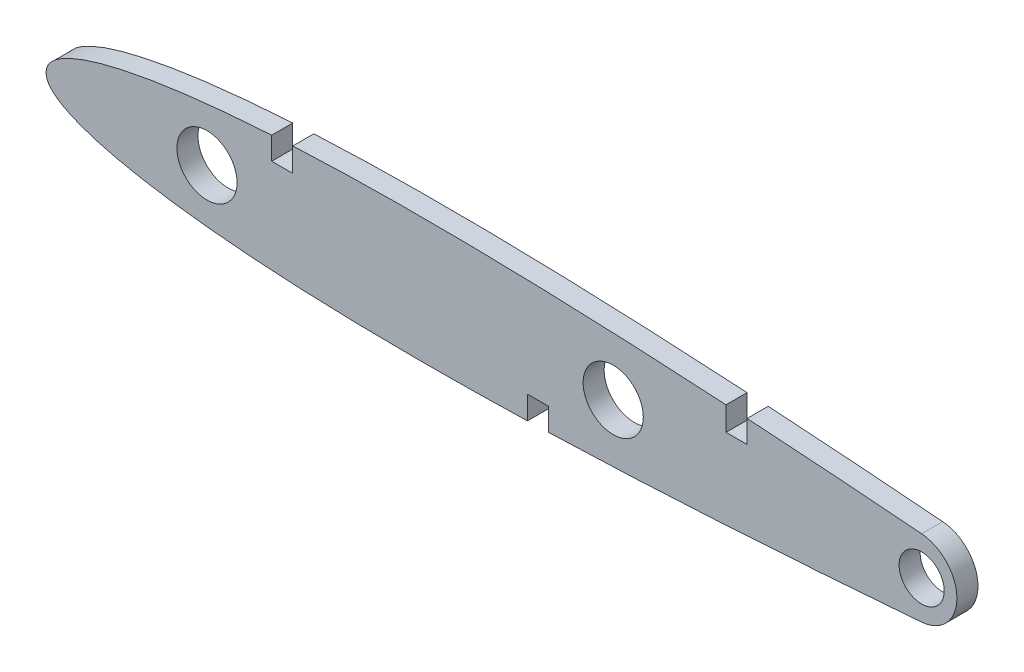
SolidWorks part; units mm, degrees
material "Фанера"
ref_plane "Спереди" through (0, 0, 0) normal (0, 0, 1) x (1, 0, 0)
ref_plane "Сверху" through (0, 0, 0) normal (0, 1, 0) x (1, 0, 0)
ref_plane "Справа" through (0, 0, 0) normal (1, 0, 0) x (0, 0, -1)
curve "Кривая1"
  spline degree 3 poles (200, 0.1747, 0) (199.6007, 0.2213, 0) (198.4854, 0.3514, 0) (196.462, 0.5838, 0) (193.7856, 0.8861, 0) (190.6579, 1.2319, 0) (187.1764, 1.6078, 0) (183.4067, 2.0045, 0) (179.3984, 2.4149, 0) (175.1909, 2.8335, 0) (170.8176, 3.2558, 0) (166.3067, 3.6778, 0) (161.6831, 4.0963, 0) (156.9692, 4.5083, 0) (152.1848, 4.9111, 0) (147.3484, 5.3022, 0) (142.4768, 5.6794, 0) (137.5855, 6.0402, 0) (132.6892, 6.3824, 0) (127.8016, 6.7038, 0) (122.9356, 7.0023, 0) (118.1034, 7.2757, 0) (113.3167, 7.5219, 0) (108.5864, 7.7388, 0) (103.9232, 7.9245, 0) (99.3373, 8.0772, 0) (94.8383, 8.1952, 0) (90.4357, 8.2769, 0) (86.1385, 8.321, 0) (81.9555, 8.3264, 0) (77.8951, 8.2921, 0) (73.9656, 8.2177, 0) (70.1749, 8.1027, 0) (66.5308, 7.947, 0) (63.0408, 7.751, 0) (59.7122, 7.515, 0) (56.5522, 7.2398, 0) (53.5677, 6.9266, 0) (50.7656, 6.5764, 0) (48.1524, 6.1907, 0) (45.7346, 5.7713, 0) (43.5185, 5.3197, 0) (41.5102, 4.8379, 0) (39.7154, 4.3278, 0) (38.1397, 3.791, 0) (36.7878, 3.2294, 0) (35.6652, 2.6441, 0) (34.771, 2.0345, 0) (34.119, 1.3968, 0) (33.6837, 0.7187, 0) (33.627, 0.2317, 0) (33.6, 0, 0) knots 0 0 0 0 0.007145 0.019956 0.036196 0.055011 0.075879 0.098429 0.122376 0.147488 0.173572 0.20046 0.228005 0.256076 0.284555 0.313333 0.34231 0.371393 0.400496 0.429538 0.458442 0.487136 0.515552 0.543624 0.57129 0.598491 0.62517 0.651272 0.676746 0.701542 0.725611 0.748908 0.771388 0.793008 0.813728 0.833508 0.85231 0.870097 0.886836 0.902493 0.917037 0.930441 0.94268 0.953734 0.96359 0.972247 0.979722 0.986065 0.991385 0.995901 1 1 1 1
curve "Кривая2"
  spline degree 3 poles (33.6, 0, 0) (33.627, -0.2317, 0) (33.6837, -0.7187, 0) (34.119, -1.3968, 0) (34.771, -2.0345, 0) (35.6652, -2.6441, 0) (36.7878, -3.2294, 0) (38.1397, -3.791, 0) (39.7154, -4.3278, 0) (41.5102, -4.8379, 0) (43.5185, -5.3197, 0) (45.7346, -5.7713, 0) (48.1524, -6.1907, 0) (50.7656, -6.5764, 0) (53.5677, -6.9266, 0) (56.5522, -7.2398, 0) (59.7122, -7.515, 0) (63.0408, -7.751, 0) (66.5308, -7.947, 0) (70.1749, -8.1027, 0) (73.9656, -8.2177, 0) (77.8951, -8.2921, 0) (81.9555, -8.3264, 0) (86.1385, -8.321, 0) (90.4357, -8.2769, 0) (94.8383, -8.1952, 0) (99.3373, -8.0772, 0) (103.9232, -7.9245, 0) (108.5864, -7.7388, 0) (113.3167, -7.5219, 0) (118.1034, -7.2757, 0) (122.9356, -7.0023, 0) (127.8016, -6.7038, 0) (132.6892, -6.3824, 0) (137.5855, -6.0402, 0) (142.4768, -5.6794, 0) (147.3484, -5.3022, 0) (152.1848, -4.9111, 0) (156.9692, -4.5083, 0) (161.6831, -4.0963, 0) (166.3067, -3.6778, 0) (170.8176, -3.2558, 0) (175.1909, -2.8335, 0) (179.3984, -2.4149, 0) (183.4067, -2.0045, 0) (187.1764, -1.6078, 0) (190.6579, -1.2319, 0) (193.7856, -0.8861, 0) (196.462, -0.5838, 0) (198.4854, -0.3514, 0) (199.6007, -0.2213, 0) (200, -0.1747, 0) knots 0 0 0 0 0.004099 0.008615 0.013935 0.020278 0.027753 0.03641 0.046266 0.05732 0.069559 0.082963 0.097507 0.113164 0.129903 0.14769 0.166492 0.186272 0.206992 0.228612 0.251092 0.274389 0.298458 0.323254 0.348728 0.37483 0.401509 0.42871 0.456376 0.484448 0.512864 0.541558 0.570462 0.599504 0.628607 0.65769 0.686667 0.715445 0.743924 0.771995 0.79954 0.826428 0.852512 0.877624 0.901571 0.924121 0.944989 0.963804 0.980044 0.992855 1 1 1 1
sketch "Эскиз1" plane through (0, 0, 0) normal (0, 0, 1) x (1, 0, 0)
  line L0 (200, 0.1747) -> (200, -0.1747)
  line L1 (97.6, -8.1212) -> (97.6, -5.0393)
  line L2 (97.6, -5.0393) -> (100.4, -5.0393)
  line L3 (100.4, -5.0393) -> (100.4, -8.0393)
  line L4 (124, 6.9352) -> (124, 3.7634)
  line L5 (124, 3.7634) -> (126.8, 3.7634)
  line L6 (126.8, 3.7634) -> (126.8, 6.7634)
  line L7 (63.6, 7.7774) -> (63.6, 4.7774)
  line L8 (63.6, 4.7774) -> (66.4, 4.7774)
  line L9 (66.4, 4.7774) -> (66.4, 7.9325)
  circle A0 centre (109, 0) radius 4
  circle A1 centre (55, 0) radius 4
  arc A2 (150, 5.0871) -> (150, -5.0871) centre (150, 0) ccw
  arc A3 (142.8797, 5.6459) -> (142.8797, -5.6459) centre (150, 0) ccw
  circle A5 centre (150, 0) radius 3
  arc A6 (150, -5.0871) -> (150, 5.0871) centre (149.5879, 0) ccw
  spline S0 degree 3 poles (-2831.395, -885.4831) (104.8143, 41.236) (28.6845, 7.0703) (34.119, -1.3968) (34.771, -2.0345) (35.6652, -2.6441) (36.7878, -3.2294) (38.1397, -3.791) (39.7154, -4.3278) (41.5102, -4.8379) (43.5185, -5.3197) (45.7346, -5.7713) (48.1524, -6.1907) (50.7656, -6.5764) (53.5677, -6.9266) (56.5522, -7.2398) (59.7122, -7.515) (63.0408, -7.751) (66.5308, -7.947) (70.1749, -8.1027) (73.9656, -8.2177) (77.8951, -8.2921) (81.9555, -8.3264) (86.1385, -8.321) (90.4357, -8.2769) (94.8383, -8.1952) (99.3373, -8.0772) (103.9232, -7.9245) (108.5864, -7.7388) (113.3167, -7.5219) (118.1034, -7.2757) (122.9356, -7.0023) (127.8016, -6.7038) (132.6892, -6.3824) (137.5855, -6.0402) (142.4768, -5.6794) (147.3484, -5.3022) (152.1848, -4.9111) (156.9692, -4.5083) (161.6831, -4.0963) (167.7684, -3.5455) (173.6854, -2.9833) (179.3984, -2.4149) (183.4067, -2.0045) (187.1764, -1.6078) (190.6579, -1.2319) (193.7856, -0.8861) (196.462, -0.5838) (290.0824, 10.1714) (381.2595, 34.0447) (818.4439, -2928.0188) knots -0.160047 -0.160047 -0.160047 -0.160047 0.004099 0.008615 0.013935 0.020278 0.027753 0.03641 0.046266 0.05732 0.069559 0.082963 0.097507 0.113164 0.129903 0.14769 0.166492 0.186272 0.206992 0.228612 0.251092 0.274389 0.298458 0.323254 0.348728 0.37483 0.401509 0.42871 0.456376 0.484448 0.512864 0.541558 0.570462 0.599504 0.628607 0.65769 0.686667 0.715445 0.743924 0.771995 0.79954 0.852512 0.877624 0.901571 0.924121 0.944989 0.963804 0.980044 0.992855 2.638559 2.638559 2.638559 2.638559 only from (33.6, 0) to (200, -0.1747) construction
  spline S1 degree 3 poles (961.5333, 3917.5463) (399.4787, -38.9514) (299.3532, -11.2364) (196.462, 0.5838) (193.7856, 0.8861) (190.6579, 1.2319) (187.1764, 1.6078) (183.4067, 2.0045) (179.3984, 2.4149) (173.6854, 2.9833) (167.7684, 3.5455) (161.6831, 4.0963) (156.9692, 4.5083) (152.1848, 4.9111) (147.3484, 5.3022) (142.4768, 5.6794) (137.5855, 6.0402) (132.6892, 6.3824) (127.8016, 6.7038) (122.9356, 7.0023) (118.1034, 7.2757) (113.3167, 7.5219) (108.5864, 7.7388) (103.9232, 7.9245) (99.3373, 8.0772) (94.8383, 8.1952) (90.4357, 8.2769) (86.1385, 8.321) (81.9555, 8.3264) (77.8951, 8.2921) (73.9656, 8.2177) (70.1749, 8.1027) (66.5308, 7.947) (63.0408, 7.751) (59.7122, 7.515) (56.5522, 7.2398) (53.5677, 6.9266) (50.7656, 6.5764) (48.1524, 6.1907) (45.7346, 5.7713) (43.5185, 5.3197) (41.5102, 4.8379) (39.7154, 4.3278) (38.1397, 3.791) (36.7878, 3.2294) (35.6652, 2.6441) (34.771, 2.0345) (34.119, 1.3968) (28.1816, -7.8538) (120.0893, -47.9948) (-3785.1012, 1186.7838) knots -1.804403 -1.804403 -1.804403 -1.804403 0.007145 0.019956 0.036196 0.055011 0.075879 0.098429 0.122376 0.147488 0.20046 0.228005 0.256076 0.284555 0.313333 0.34231 0.371393 0.400496 0.429538 0.458442 0.487136 0.515552 0.543624 0.57129 0.598491 0.62517 0.651272 0.676746 0.701542 0.725611 0.748908 0.771388 0.793008 0.813728 0.833508 0.85231 0.870097 0.886836 0.902493 0.917037 0.930441 0.94268 0.953734 0.96359 0.972247 0.979722 0.986065 0.991385 0.995901 1.176146 1.176146 1.176146 1.176146 only from (200, 0.1747) to (33.6, 0) construction
  spline S2 degree 3 poles (33.6, 0) (33.627, -0.2317) (33.6837, -0.7187) (34.119, -1.3968) (34.771, -2.0345) (35.6652, -2.6441) (36.7878, -3.2294) (38.1397, -3.791) (39.7154, -4.3278) (41.5102, -4.8379) (43.5185, -5.3197) (45.7346, -5.7713) (48.1524, -6.1907) (50.7656, -6.5764) (53.5677, -6.9266) (56.5522, -7.2398) (59.7122, -7.515) (63.0408, -7.751) (66.5308, -7.947) (70.1749, -8.1027) (73.9656, -8.2177) (77.8951, -8.2921) (81.9555, -8.3264) (86.1385, -8.321) (90.4357, -8.2769) (94.2689, -8.2058) (96.6686, -8.1464) (97.6, -8.1212) knots 0 0 0 0 0.004099 0.008615 0.013935 0.020278 0.027753 0.03641 0.046266 0.05732 0.069559 0.082963 0.097507 0.113164 0.129903 0.14769 0.166492 0.186272 0.206992 0.228612 0.251092 0.274389 0.298458 0.323254 0.348728 0.37483 0.391389 0.391389 0.391389 0.391389
  spline S3 degree 3 poles (200, 0.1747) (199.6007, 0.2213) (198.4854, 0.3514) (196.462, 0.5838) (193.7856, 0.8861) (190.6579, 1.2319) (187.1764, 1.6078) (183.4067, 2.0045) (179.3984, 2.4149) (173.6854, 2.9833) (167.7684, 3.5455) (161.6831, 4.0963) (156.9692, 4.5083) (152.1848, 4.9111) (147.3484, 5.3022) (142.4768, 5.6794) (137.5855, 6.0402) (132.6892, 6.3824) (129.0934, 6.6189) (127.1312, 6.7427) (126.8, 6.7634) knots 0 0 0 0 0.007145 0.019956 0.036196 0.055011 0.075879 0.098429 0.122376 0.147488 0.20046 0.228005 0.256076 0.284555 0.313333 0.34231 0.371393 0.400496 0.429538 0.435436 0.435436 0.435436 0.435436
  spline S4 degree 3 poles (124, 6.9352) (123.6412, 6.9567) (121.6707, 7.0739) (118.1034, 7.2757) (113.3167, 7.5219) (108.5864, 7.7388) (103.9232, 7.9245) (99.3373, 8.0772) (94.8383, 8.1952) (90.4357, 8.2769) (86.1385, 8.321) (81.9555, 8.3264) (77.8951, 8.2921) (73.9656, 8.2177) (70.1749, 8.1027) (67.6688, 7.9956) (66.4269, 7.9339) (66.4, 7.9325) knots 0.452054 0.452054 0.452054 0.452054 0.458442 0.487136 0.515552 0.543624 0.57129 0.598491 0.62517 0.651272 0.676746 0.701542 0.725611 0.748908 0.771388 0.793008 0.793486 0.793486 0.793486 0.793486
  spline S5 degree 3 poles (100.4, -8.0393) (101.5657, -8.0027) (104.2872, -7.91) (108.5864, -7.7388) (113.3167, -7.5219) (118.1034, -7.2757) (122.9356, -7.0023) (127.8016, -6.7038) (132.6892, -6.3824) (137.5855, -6.0402) (142.4768, -5.6794) (147.3484, -5.3022) (152.1848, -4.9111) (156.9692, -4.5083) (161.6831, -4.0963) (167.7684, -3.5455) (173.6854, -2.9833) (179.3984, -2.4149) (183.4067, -2.0045) (187.1764, -1.6078) (190.6579, -1.2319) (193.7856, -0.8861) (196.462, -0.5838) (198.4854, -0.3514) (199.6007, -0.2213) (200, -0.1747) knots 0.407983 0.407983 0.407983 0.407983 0.42871 0.456376 0.484448 0.512864 0.541558 0.570462 0.599504 0.628607 0.65769 0.686667 0.715445 0.743924 0.771995 0.79954 0.852512 0.877624 0.901571 0.924121 0.944989 0.963804 0.980044 0.992855 1 1 1 1
  spline S6 degree 3 poles (63.6, 7.7774) (63.3962, 7.765) (62.0815, 7.683) (59.7122, 7.515) (56.5522, 7.2398) (53.5677, 6.9266) (50.7656, 6.5764) (48.1524, 6.1907) (45.7346, 5.7713) (43.5185, 5.3197) (41.5102, 4.8379) (39.7154, 4.3278) (38.1397, 3.791) (36.7878, 3.2294) (35.6652, 2.6441) (34.771, 2.0345) (34.119, 1.3968) (33.6837, 0.7187) (33.627, 0.2317) (33.6, 0) knots 0.810099 0.810099 0.810099 0.810099 0.813728 0.833508 0.85231 0.870097 0.886836 0.902493 0.917037 0.930441 0.94268 0.953734 0.96359 0.972247 0.979722 0.986065 0.991385 0.995901 1 1 1 1
  point P14 (99, -5.0393)
  point P20 (65, 4.7774)
  dimension "D1" = 8
  dimension "D2" = 8
  dimension "D16" = 5.0871
  dimension "D17" = 9.0871
  dimension "D18" = 6
  dimension "D3" = 75.4
  dimension "D4" = 21.4
  dimension "D5" = 2.8
  dimension "D6" = 2.8
  dimension "D7" = 10
  dimension "D8" = 15
  dimension "D9" = 3
  dimension "D10" = 3
  dimension "D11" = 2.8
  dimension "D12" = 10
  dimension "D13" = 3
  dimension "D14" = 116.4
  dimension "D15" = 10.1742
extrude "Бобышка-Вытянуть1" add sketch "Эскиз1" along normal mid plane 2.8 contours L7 S6 S2 L1 L2 L3 S5 A3 S3 L6 L5 L4 S4 L9 L8 A0 A1 | A3 S5 A2 S3 | A2 A6 A5
equation "\"D3@Эскиз1\"=109-33.6"
equation "\"D16@Эскиз1\"=\"D15@Эскиз1\"/2"
equation "\"D17@Эскиз1\"=\"D16@Эскиз1\"+4"
